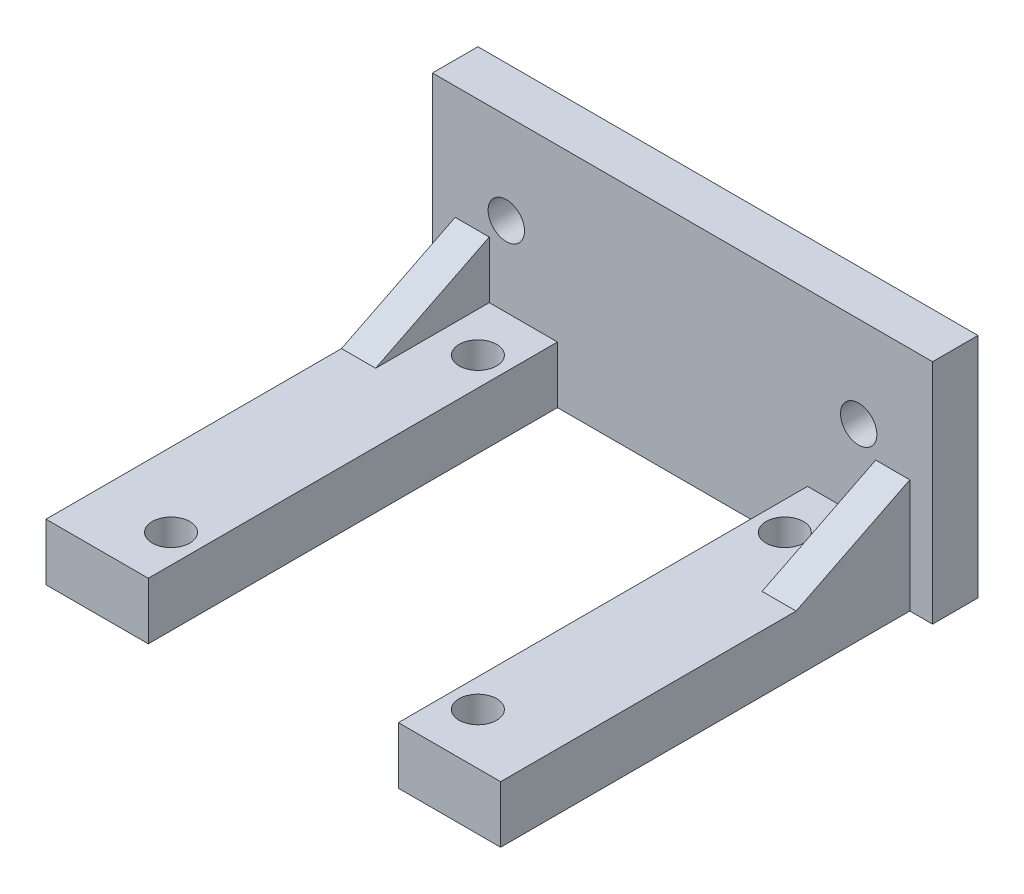
SolidWorks part; units mm, degrees
ref_plane "前视基准面" through (0, 0, 0) normal (0, 0, 1) x (1, 0, 0)
ref_plane "上视基准面" through (0, 0, 0) normal (0, 1, 0) x (1, 0, 0)
ref_plane "右视基准面" through (0, 0, 0) normal (1, 0, 0) x (0, 0, -1)
sketch "草图1" plane through (0, 0, 0) normal (0, 1, 0) x (1, 0, 0)
  line L0 (0, 26.0436) -> (0, -39.6587) construction
  line L1 (-20, 20) -> (20, 20)
  line L2 (-20, 20) -> (-20, -20)
  line L3 (-20, -20) -> (-11, -20)
  line L4 (20, 20) -> (20, -20)
  line L5 (-20, 20) -> (20, -20) construction
  line L6 (-20, -20) -> (20, 20) construction
  line L7 (11, -20) -> (20, -20)
  line L8 (-11, 16) -> (11, 16)
  line L9 (-11, 16) -> (-11, -20)
  line L11 (11, 16) -> (11, -20)
  line L12 (-11, 16) -> (11, -20) construction
  line L13 (-11, -20) -> (11, 16) construction
  line L14 (-13.5, -15.5) -> (13.5, -15.5) construction
  line L15 (-22.0727, -2) -> (30.5952, -2) construction
  line L16 (-13.5, 11.5) -> (13.5, 11.5) construction
  circle A0 centre (-13.5, -15.5) radius 1.65
  circle A1 centre (13.5, -15.5) radius 1.65
  circle A2 centre (13.5, 11.5) radius 1.65
  circle A3 centre (-13.5, 11.5) radius 1.65
  point P0 (0, 0)
  point P12 (0, -2)
  dimension "D3" = 3.3
  dimension "D1" = 40
  dimension "D2" = 27
  dimension "D4" = 40
  dimension "D5" = 22
  dimension "D6" = 4
  dimension "D7" = 27
extrude "凸台-拉伸1" add sketch "草图1" along normal blind 5
sketch "草图2" plane through (0, 0, -20) normal (0, 0, -1) x (-1, 0, 0)
  line L0 (0, 20.4528) -> (0, 0) construction
  line L1 (-20, 0) -> (20, 0) construction
  line L2 (-22, 20) -> (22, 20)
  line L3 (-22, 20) -> (-22, 0)
  line L4 (-22, 0) -> (22, 0)
  line L5 (22, 20) -> (22, 0)
  line L6 (-22, 20) -> (22, 0) construction
  line L7 (-22, 0) -> (22, 20) construction
  line L8 (-15.5, 12) -> (15.5, 12) construction
  circle A0 centre (-15.5, 12) radius 1.6
  circle A1 centre (15.5, 12) radius 1.6
  point P3 (0, 10)
  dimension "D5" = 3.2
  dimension "D1" = 44
  dimension "D2" = 31
  dimension "D3" = 12
  dimension "D4" = 20
extrude "凸台-拉伸2" add sketch "草图2" against normal blind 4
sketch "草图4" plane through (-20, 0, 0) normal (-1, 0, 0) x (0, 0, 1)
  line L0 (-16, 0) -> (-6, 5)
  line L1 (-16, 5) -> (-16, 0) construction
  line L2 (-16, 5) -> (20, 5) construction
  line L3 (-6, 5) -> (-16, 5)
  line L4 (-16, 5) -> (-16, 0)
  dimension "D1" = 5
  dimension "D2" = 10
extrude "凸台-拉伸4" add sketch "草图4" against normal blind 3
sketch "草图5" plane through (20, 0, 0) normal (1, 0, 0) x (0, 0, -1)
  line L0 (16, 10) -> (6, 5)
  line L1 (6, 5) -> (16, 5)
  line L2 (16, 5) -> (16, 10)
  point P6 (0, 0)
  point P7 (0, 0)
  dimension "D1" = 5
  dimension "D2" = 10
extrude "凸台-拉伸5" add sketch "草图5" against normal blind 3
sketch "草图6" plane through (-20, 0, 0) normal (-1, 0, 0) x (0, 0, 1)
  line L0 (-16, 10) -> (-16, 5)
  line L1 (-16, 0) -> (-16, 20) construction
  line L2 (-16, 5) -> (-6, 5)
  line L3 (-6, 5) -> (-16, 10)
extrude "凸台-拉伸6" add sketch "草图6" against normal blind 3
